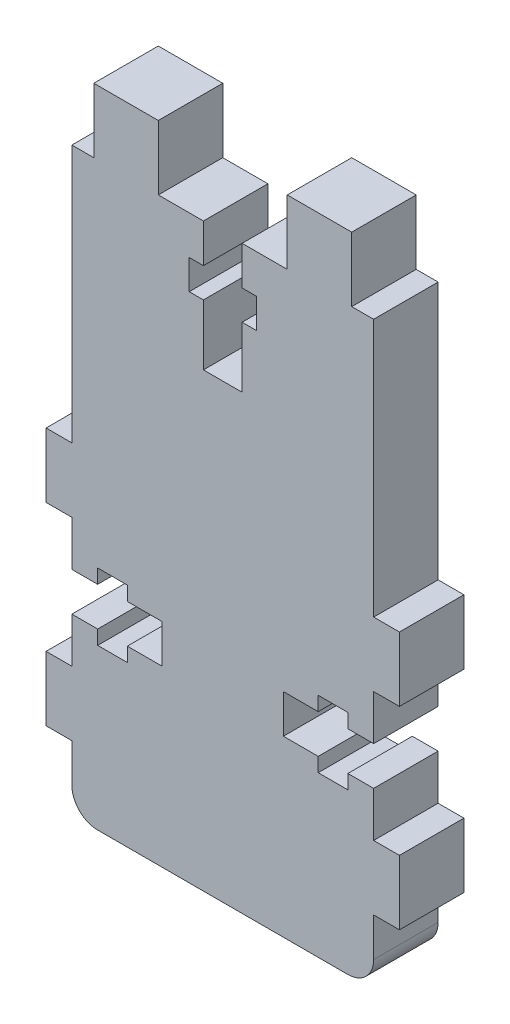
SolidWorks part; units mm, degrees
ref_plane "Plan de face" through (0, 0, 0) normal (0, 0, 1) x (1, 0, 0)
ref_plane "Plan de dessus" through (0, 0, 0) normal (0, 1, 0) x (1, 0, 0)
ref_plane "Plan de droite" through (0, 0, 0) normal (1, 0, 0) x (0, 0, -1)
sketch "Esquisse1" plane through (0, 0, 0) normal (0, 0, 1) x (1, 0, 0)
  line L0 (0, 0) -> (0, 45) construction
  line L1 (0, 45) -> (23.4, 45) construction
  line L2 (23.4, 45) -> (23.4, 0) construction
  line L3 (23.4, 0) -> (0, 0) construction
  line L4 (0, 15) -> (23.4, 15) construction
  line L5 (1.7, 45) -> (0, 45)
  line L6 (0, 45) -> (0, 25)
  line L7 (21.7, 45) -> (23.4, 45)
  line L8 (23.4, 45) -> (23.4, 25)
  line L9 (23.4, 5) -> (23.4, 0)
  line L10 (0, 0) -> (23.4, 0)
  line L12 (0, 0) -> (0, 5)
  line B0 (9.1, 42) -> (9.1, 39.7)
  line B1 (13.2, 39.7) -> (13.2, 35)
  line B2 (10.2, 35) -> (10.2, 39.7)
  line B3 (9.1, 39.7) -> (10.2, 39.7)
  line B4 (11.7, 45) -> (11.7, 33.7792) construction
  line B5 (10.2, 45) -> (6.7, 45)
  line B6 (6.7, 50) -> (1.7, 50)
  line B7 (1.7, 50) -> (1.7, 45)
  line B8 (6.7, 50) -> (6.7, 45)
  line B9 (13.2, 45) -> (16.7, 45)
  line B10 (16.7, 45) -> (16.7, 50)
  line B11 (16.7, 50) -> (21.7, 50)
  line B12 (21.7, 50) -> (21.7, 45)
  line B13 (10.2, 45) -> (13.2, 45) construction
  line B14 (13.2, 45) -> (13.2, 42)
  line B15 (13.2, 39.7) -> (14.3, 39.7)
  line B16 (14.3, 42) -> (13.2, 42)
  line B17 (13.2, 35) -> (10.2, 35)
  line B18 (10.2, 42) -> (9.1, 42)
  line B19 (14.3, 39.7) -> (14.3, 42)
  line B20 (10.2, 42) -> (10.2, 45)
  line B21 (11.7, 35) -> (11.7, 45) construction
  line B22 (23.3419, 15) -> (9.4468, 15) construction
  line B23 (23.4, 13.5) -> (23.4, 10)
  line B24 (25.4, 10) -> (25.4, 5)
  line B25 (25.4, 5) -> (23.4, 5)
  line B26 (25.4, 10) -> (23.4, 10)
  line B27 (23.4, 16.2928) -> (23.4, 20)
  line B28 (23.4, 20) -> (25.4, 20)
  line B29 (25.4, 20) -> (25.4, 25)
  line B30 (25.4, 25) -> (23.4, 25)
  line B31 (23.4, 13.5) -> (23.4, 16.5) construction
  line B32 (23.4, 16.5) -> (21.4, 16.5)
  line B33 (19.1, 16.5) -> (19.1, 17.6)
  line B34 (21.4, 12.4) -> (19.1, 12.4)
  line B35 (21.4, 17.6) -> (21.4, 16.5)
  line B36 (19.1, 16.5) -> (16.4, 16.5)
  line B37 (16.4, 16.5) -> (16.4, 13.5)
  line B38 (16.4, 13.5) -> (19.1, 13.5)
  line B39 (21.4, 13.5) -> (21.4, 12.4)
  line B40 (19.1, 17.6) -> (21.4, 17.6)
  line B41 (19.1, 12.4) -> (19.1, 13.5)
  line B42 (21.4, 13.5) -> (23.4, 13.5)
  line B43 (16.4, 15) -> (23.4, 15) construction
  line B44 (0.0581, 15) -> (13.9532, 15) construction
  line B45 (0, 13.5) -> (0, 10)
  line B46 (-2, 10) -> (-2, 5)
  line B47 (-2, 5) -> (0, 5)
  line B48 (-2, 10) -> (0, 10)
  line B49 (0, 16.2928) -> (0, 20)
  line B50 (0, 20) -> (-2, 20)
  line B51 (-2, 20) -> (-2, 25)
  line B52 (-2, 25) -> (0, 25)
  line B53 (0, 13.5) -> (0, 16.5) construction
  line B54 (0, 16.5) -> (2, 16.5)
  line B55 (4.3, 16.5) -> (4.3, 17.6)
  line B56 (2, 12.4) -> (4.3, 12.4)
  line B57 (2, 17.6) -> (2, 16.5)
  line B58 (4.3, 16.5) -> (7, 16.5)
  line B59 (7, 16.5) -> (7, 13.5)
  line B60 (7, 13.5) -> (4.3, 13.5)
  line B61 (2, 13.5) -> (2, 12.4)
  line B62 (4.3, 17.6) -> (2, 17.6)
  line B63 (4.3, 12.4) -> (4.3, 13.5)
  line B64 (2, 13.5) -> (0, 13.5)
  line B65 (7, 15) -> (0, 15) construction
  dimension "D1" = 23.4
  dimension "D2" = 15
  dimension "D3" = 30
sketch_block_instance "Insert M3 plots ep 5mm-13"
sketch_block "Insert M3 plots ep 5mm" parameters "D1"=10, "D2"=5, "D3"=5
sketch_block_instance "Decoupe Insert M3-4"
sketch_block "Decoupe Insert M3" parameters "D1"=5.2, "D2"=3, "D3"=2.3, "D4"=3, "D5"=10
sketch_block_instance "Bloc1-1"
sketch_block "Bloc1" parameters "D1"=10, "D2"=5, "D3"=2
sketch_block_instance "Bloc3-3"
sketch_block "Bloc3" parameters "D1"=5.2, "D2"=3, "D3"=2.3, "D4"=2, "D5"=7
sketch_block_instance "Bloc1-3"
extrude "Boss.-Extru.1" add sketch "Esquisse1" along normal blind 5
fillet "Fillet1" radius 2 2 edges at (0, 0, 2.5) (23.4, 0, 2.5)
